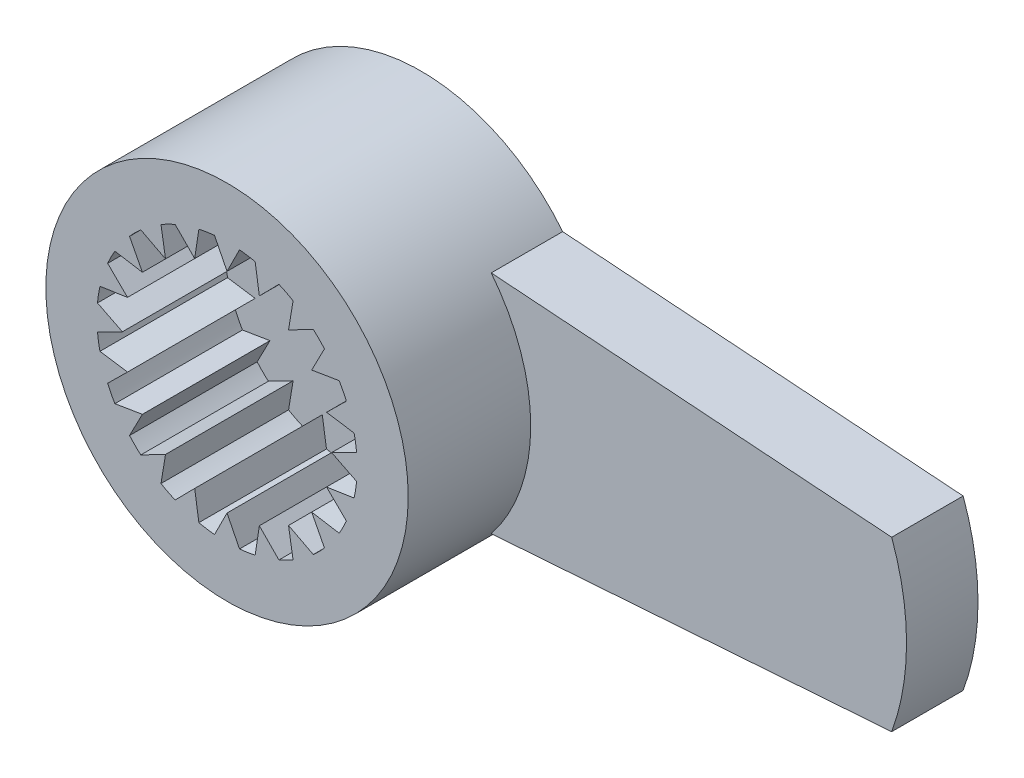
SolidWorks part; units mm, degrees
ref_plane "Front Plane" through (0, 0, 0) normal (0, 0, 1) x (1, 0, 0)
ref_plane "Top Plane" through (0, 0, 0) normal (0, 1, 0) x (1, 0, 0)
ref_plane "Right Plane" through (0, 0, 0) normal (1, 0, 0) x (0, 0, -1)
sketch "Sketch2" plane through (0, 0, 0) normal (0, 0, 1) x (1, 0, 0)
  circle A0 centre (0, 0) radius 3.55
  dimension "D1" = 7.1
sketch "Sketch3" plane through (0, 0, 0) normal (0, 0, 1) x (1, 0, 0)
  line L0 (-0.2447, 2.5382) -> (0, 2.05)
  line L1 (0, 2.05) -> (0.2447, 2.5382)
  line L2 (0.5516, 2.4896) -> (0.6335, 1.9497)
  line L3 (0.6335, 1.9497) -> (1.0171, 2.3384)
  line L4 (1.294, 2.1973) -> (1.205, 1.6585)
  line L5 (1.205, 1.6585) -> (1.6899, 1.9096)
  line L6 (1.9096, 1.6899) -> (1.6585, 1.205)
  line L7 (1.6585, 1.205) -> (2.1973, 1.294)
  line L8 (2.3384, 1.0171) -> (1.9497, 0.6335)
  line L9 (1.9497, 0.6335) -> (2.4896, 0.5516)
  line L10 (2.5382, 0.2447) -> (2.05, 0)
  line L11 (2.05, 0) -> (2.5382, -0.2447)
  line L12 (2.4896, -0.5516) -> (1.9497, -0.6335)
  line L13 (1.9497, -0.6335) -> (2.3384, -1.0171)
  line L14 (2.1973, -1.294) -> (1.6585, -1.205)
  line L15 (1.6585, -1.205) -> (1.9096, -1.6899)
  line L16 (1.6899, -1.9096) -> (1.205, -1.6585)
  line L17 (1.205, -1.6585) -> (1.294, -2.1973)
  line L18 (1.0171, -2.3384) -> (0.6335, -1.9497)
  line L19 (0.6335, -1.9497) -> (0.5516, -2.4896)
  line L20 (0.2447, -2.5382) -> (0, -2.05)
  line L21 (0, -2.05) -> (-0.2447, -2.5382)
  line L22 (-0.5516, -2.4896) -> (-0.6335, -1.9497)
  line L23 (-0.6335, -1.9497) -> (-1.0171, -2.3384)
  line L24 (-1.294, -2.1973) -> (-1.205, -1.6585)
  line L25 (-1.205, -1.6585) -> (-1.6899, -1.9096)
  line L26 (-1.9096, -1.6899) -> (-1.6585, -1.205)
  line L27 (-1.6585, -1.205) -> (-2.1973, -1.294)
  line L28 (-2.3384, -1.0171) -> (-1.9497, -0.6335)
  line L29 (-1.9497, -0.6335) -> (-2.4896, -0.5516)
  line L30 (-2.5382, -0.2447) -> (-2.05, 0)
  line L31 (-2.05, 0) -> (-2.5382, 0.2447)
  line L32 (-2.4896, 0.5516) -> (-1.9497, 0.6335)
  line L33 (-1.9497, 0.6335) -> (-2.3384, 1.0171)
  line L34 (-2.1973, 1.294) -> (-1.6585, 1.205)
  line L35 (-1.6585, 1.205) -> (-1.9096, 1.6899)
  line L36 (-1.6899, 1.9096) -> (-1.205, 1.6585)
  line L37 (-1.205, 1.6585) -> (-1.294, 2.1973)
  line L38 (-1.0171, 2.3384) -> (-0.6335, 1.9497)
  line L39 (-0.6335, 1.9497) -> (-0.5516, 2.4896)
  arc A0 (-0.2447, 2.5382) -> (0.2447, 2.5382) centre (0, 0) cw
  arc A2 (0.5516, 2.4896) -> (1.0171, 2.3384) centre (0, 0) cw
  arc A3 (1.294, 2.1973) -> (1.6899, 1.9096) centre (0, 0) cw
  arc A4 (1.9096, 1.6899) -> (2.1973, 1.294) centre (0, 0) cw
  arc A5 (2.3384, 1.0171) -> (2.4896, 0.5516) centre (0, 0) cw
  arc A6 (2.5382, 0.2447) -> (2.5382, -0.2447) centre (0, 0) cw
  arc A7 (2.4896, -0.5516) -> (2.3384, -1.0171) centre (0, 0) cw
  arc A8 (2.1973, -1.294) -> (1.9096, -1.6899) centre (0, 0) cw
  arc A9 (1.6899, -1.9096) -> (1.294, -2.1973) centre (0, 0) cw
  arc A10 (1.0171, -2.3384) -> (0.5516, -2.4896) centre (0, 0) cw
  arc A11 (0.2447, -2.5382) -> (-0.2447, -2.5382) centre (0, 0) cw
  arc A12 (-0.5516, -2.4896) -> (-1.0171, -2.3384) centre (0, 0) cw
  arc A13 (-1.294, -2.1973) -> (-1.6899, -1.9096) centre (0, 0) cw
  arc A14 (-1.9096, -1.6899) -> (-2.1973, -1.294) centre (0, 0) cw
  arc A15 (-2.3384, -1.0171) -> (-2.4896, -0.5516) centre (0, 0) cw
  arc A16 (-2.5382, -0.2447) -> (-2.5382, 0.2447) centre (0, 0) cw
  arc A17 (-2.4896, 0.5516) -> (-2.3384, 1.0171) centre (0, 0) cw
  arc A18 (-2.1973, 1.294) -> (-1.9096, 1.6899) centre (0, 0) cw
  arc A19 (-1.6899, 1.9096) -> (-1.294, 2.1973) centre (0, 0) cw
  arc A20 (-1.0171, 2.3384) -> (-0.5516, 2.4896) centre (0, 0) cw
  point P66 (0, 0)
  dimension "D1" = 20
ref_plane "Plane1" through (0, 0, -2.4) normal (0, 0, 1) x (1, 0, 0)
sketch "Sketch4" plane through (0, 0, -2.4) normal (0, 0, 1) x (1, 0, 0)
  line L0 (2.7764, 2.2123) -> (10.6226, 1.65)
  line L1 (2.7764, -2.2123) -> (10.6226, -1.65)
  arc A0 (10.6226, 1.65) -> (10.6226, -1.65) centre (6.0891, 0) cw
  arc A1 (2.7764, 2.2123) -> (2.7764, -2.2123) centre (0, 0) cw
  point P9 (10.6226, 1.65)
extrude "Boss-Extrude1" add sketch "Sketch2" against normal blind 3.8 contours A0
extrude "Boss-Extrude2" add sketch "Sketch4" against normal blind 1.4
sketch "Sketch5" plane through (0, 0, 0) normal (0, 0, 1) x (1, 0, 0)
  circle A0 centre (0, 0) radius 2.55
extrude "Cut-Extrude1" cut sketch "Sketch5" against normal blind 2.5
extrude "Boss-Extrude3" add sketch "Sketch3" against normal up to surface (2.5 mm away) up to face at (2.55, 0, -2.5)
